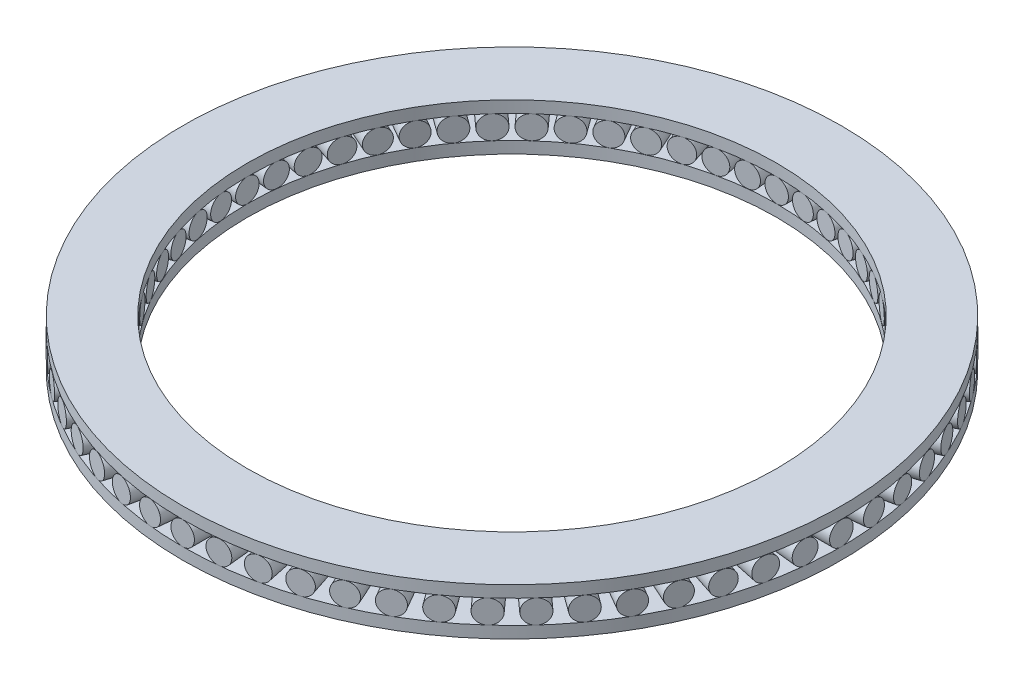
SolidWorks part; units mm, degrees
ref_plane "前视基准面" through (0, 0, 0) normal (0, 0, 1) x (1, 0, 0)
ref_plane "上视基准面" through (0, 0, 0) normal (0, 1, 0) x (1, 0, 0)
ref_plane "右视基准面" through (0, 0, 0) normal (1, 0, 0) x (0, 0, -1)
sketch "草图1" plane through (0, 0, 0) normal (0, 1, 0) x (1, 0, 0)
  circle A0 centre (0, 0) radius 28
  circle A1 centre (0, 0) radius 22.5
  dimension "D1" = 45
  dimension "D2" = 56
extrude "凸台-拉伸1" add sketch "草图1" along normal blind 1
sketch "草图2" plane through (0, 0, 0) normal (0, 0, 1) x (1, 0, 0)
  circle A0 centre (0, 2) radius 1
extrude "凸台-拉伸2" add sketch "草图2" along normal blind 5.5 from offset 22.5 separate body
pattern_circular "阵列(圆周)3" count 60 every 6 about axis through (0, 0, 0) along (0, 1, 0) of bodies 102
sketch "草图3" plane through (0, 0, 0) normal (0, -1, 0) x (1, 0, 0)
  circle A0 centre (0, 0) radius 28
  circle A1 centre (0, 0) radius 22.5
  dimension "D1" = 45
  dimension "D2" = 56
extrude "凸台-拉伸3" add sketch "草图3" against normal blind 1 from offset 3 separate body
